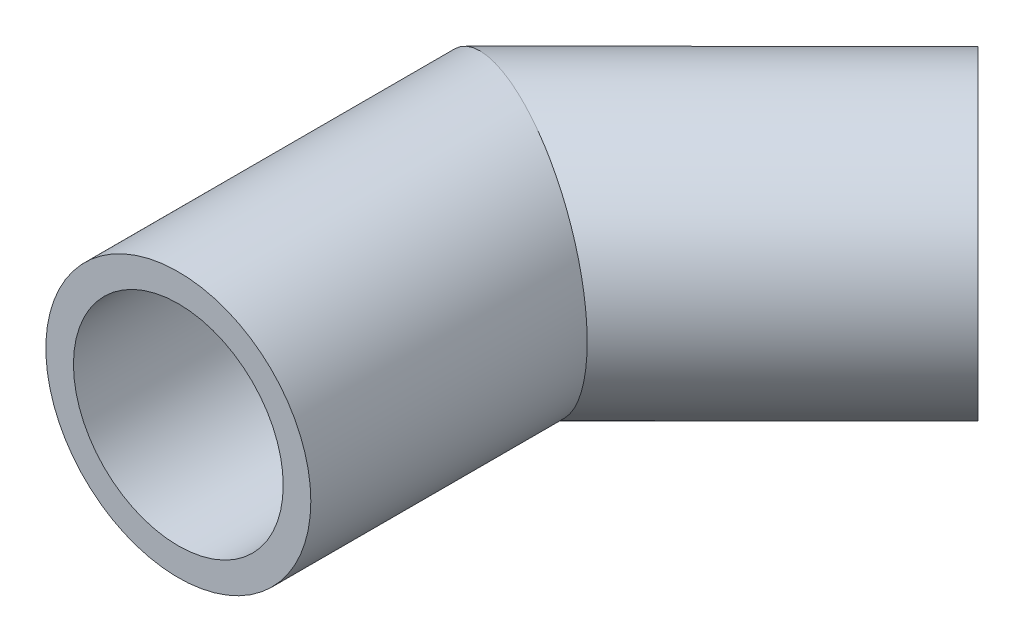
SolidWorks part; units mm, degrees
material "PVC Rigid"
ref_plane "Front Plane" through (0, 0, 0) normal (0, 0, 1) x (1, 0, 0)
ref_plane "Top Plane" through (0, 0, 0) normal (0, 1, 0) x (1, 0, 0)
ref_plane "Right Plane" through (0, 0, 0) normal (1, 0, 0) x (0, 0, -1)
sketch "Sketch2" plane through (0, 0, 0) normal (0, 1, 0) x (1, 0, 0)
  line L0 (0, 0) -> (0, 76.2)
  line L1 (0, 76.2) -> (53.8815, 130.0815)
  dimension "D1" = 76.2
  dimension "D2" = 76.2
  dimension "D3" = 135
sketch "Sketch3" plane through (0, 0, 0) normal (0, 0, 1) x (1, 0, 0)
  circle A0 centre (0, 0) radius 24.13
  circle A1 centre (0, 0) radius 30.48
  dimension "D1" = 6.35
  dimension "D2" = 48.26
sweep "Sweep1" add profiles "Sketch3" path "Sketch2"
